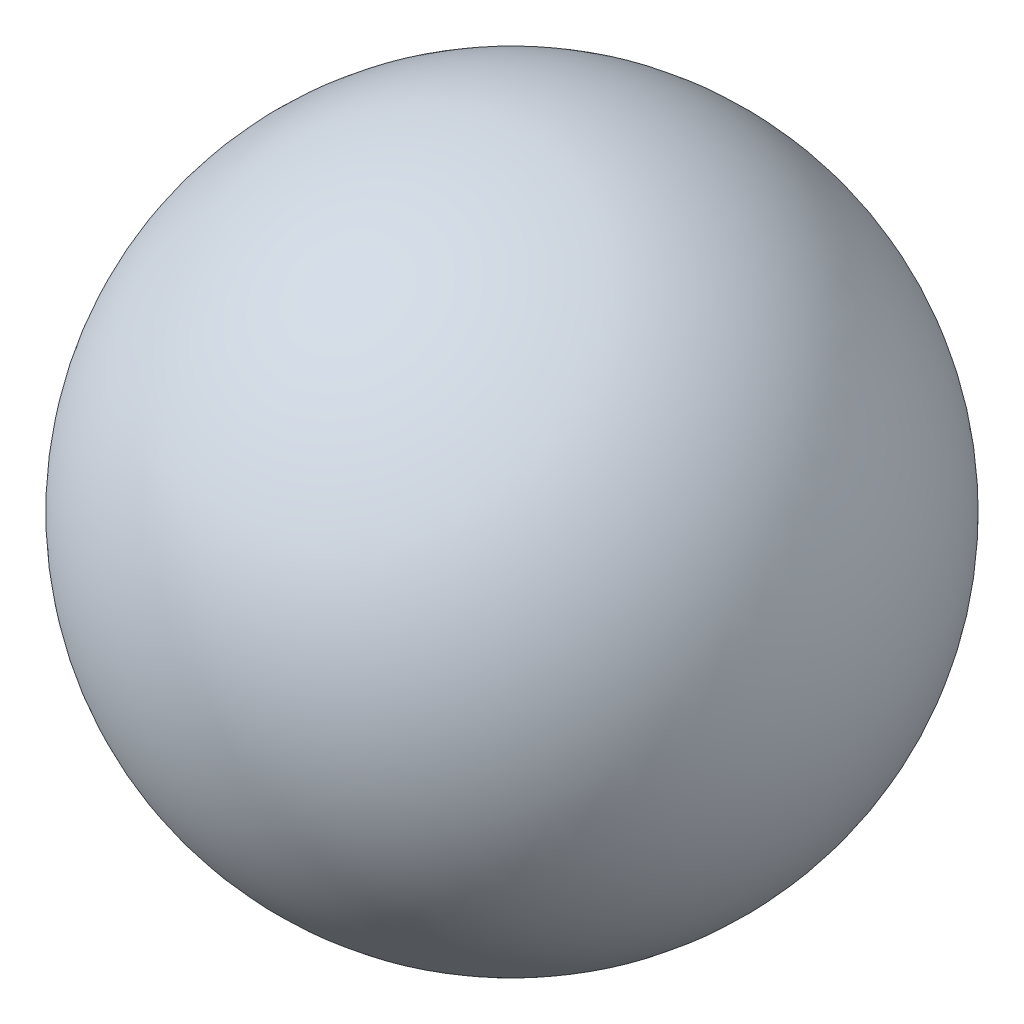
SolidWorks part; units mm, degrees
ref_plane "Front Plane" through (0, 0, 0) normal (0, 0, 1) x (1, 0, 0)
ref_plane "Top Plane" through (0, 0, 0) normal (0, 1, 0) x (1, 0, 0)
ref_plane "Right Plane" through (0, 0, 0) normal (1, 0, 0) x (0, 0, -1)
ref_axis "Axis1" through (0, -22, 0) along (0, 1, 0)
sketch "Sketch2" plane through (0, 0, 0) normal (0, 0, 1) x (1, 0, 0)
  line L0 (0, -22) -> (0, 22) construction
  line L1 (0, 100) -> (0, -100)
  arc A0 (0, 100) -> (0, -100) centre (0, 0) ccw
  dimension "D1" = 100
revolve "Revolve2" add sketch "Sketch2" angle 360 about axis through (0, -22, 0) along (0, 1, 0)
equation "\"radius\"=100"
equation "\"D1@Sketch2\"=\"radius\""
